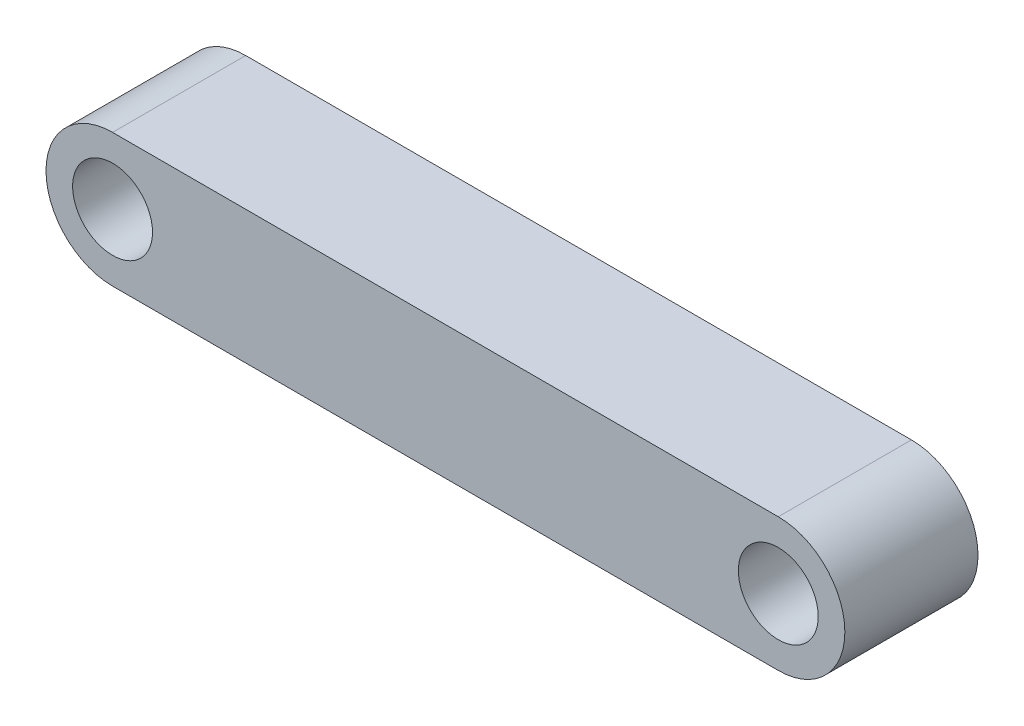
SolidWorks part; units mm, degrees
ref_plane "Front Plane" through (0, 0, 0) normal (0, 0, 1) x (1, 0, 0)
ref_plane "Top Plane" through (0, 0, 0) normal (0, 1, 0) x (1, 0, 0)
ref_plane "Right Plane" through (0, 0, 0) normal (1, 0, 0) x (0, 0, -1)
sketch "Sketch1" plane through (0, 0, 0) normal (0, 0, 1) x (1, 0, 0)
  line L1 (50, -10) -> (-50, -10)
  line L3 (50, 10) -> (-50, 10)
  line L5 (50, -10) -> (-50, 10) construction
  line L6 (50, 10) -> (-50, -10) construction
  arc A0 (-50, 10) -> (-50, -10) centre (-50, 0) ccw
  arc A1 (50, 10) -> (50, -10) centre (50, 0) cw
  point P0 (0, 0)
  point P7 (-60, 0)
  point P9 (60, 0)
  dimension "D3" = 120
  dimension "D1" = 100
  dimension "D2" = 20
extrude "Boss-Extrude1" add sketch "Sketch1" along normal blind 20
sketch "Sketch2" plane through (0, 0, 20) normal (0, 0, 1) x (1, 0, 0)
  circle A0 centre (-50, 0) radius 6
  circle A1 centre (50, 0) radius 6
  dimension "D1" = 12
extrude "Cut-Extrude1" cut sketch "Sketch2" against normal through all
